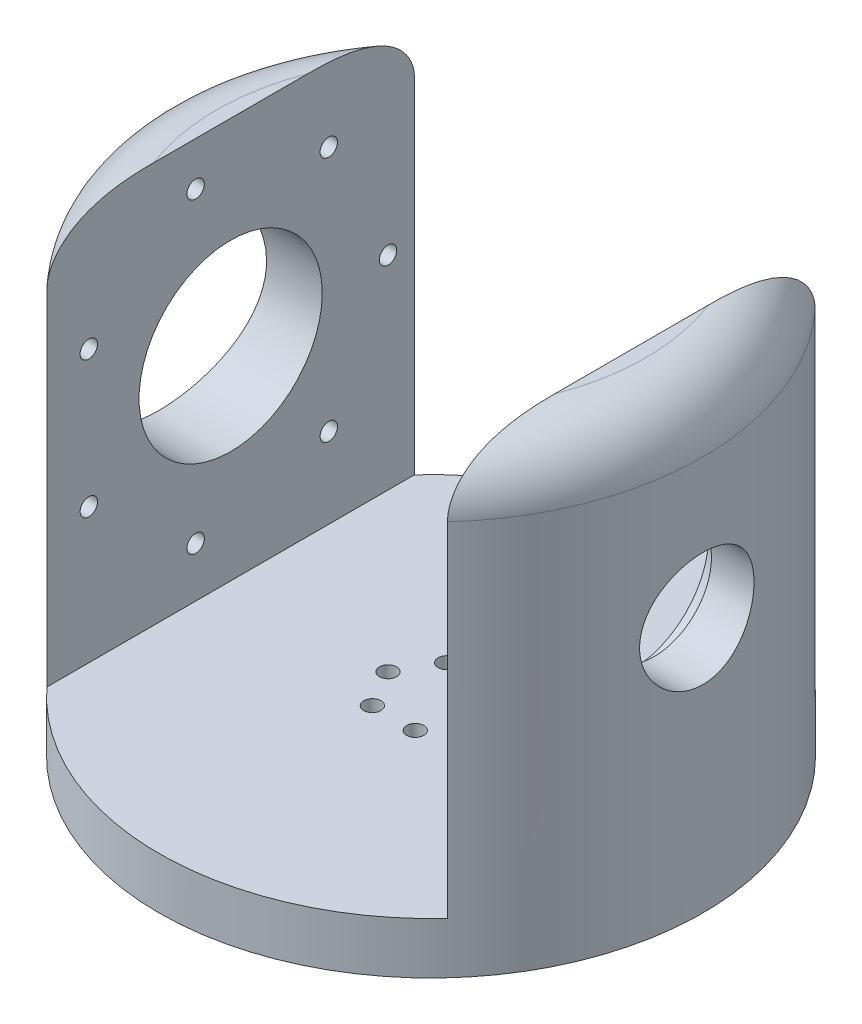
SolidWorks part; units mm, degrees
ref_plane "Alzado" through (0, 0, 0) normal (0, 0, 1) x (1, 0, 0)
ref_plane "Planta" through (0, 0, 0) normal (0, 1, 0) x (1, 0, 0)
ref_plane "Vista lateral" through (0, 0, 0) normal (1, 0, 0) x (0, 0, -1)
sketch "Croquis1" plane through (0, 0, 0) normal (0, 1, 0) x (1, 0, 0)
  circle A0 centre (0, 0) radius 47.5
  circle A1 centre (0, 0) radius 10
  dimension "D1" = 95
  dimension "D2" = 20
extrude "Saliente-Extruir1" add sketch "Croquis1" along normal blind 6
sketch "Croquis2" plane through (0, 6, 0) normal (0, 1, 0) x (1, 0, 0)
  circle A0 centre (0, 0) radius 47.5
  circle A1 centre (0, 0) radius 7.5 construction
  circle A2 centre (7.5, 0) radius 1.5
  circle A3 centre (3.75, -6.4952) radius 1.5
  circle A4 centre (-3.75, -6.4952) radius 1.5
  circle A5 centre (-7.5, 0) radius 1.5
  circle A6 centre (-3.75, 6.4952) radius 1.5
  circle A7 centre (3.75, 6.4952) radius 1.5
  point P18 (0, 0)
  dimension "D1" = 95
  dimension "D2" = 15
  dimension "D3" = 3
  dimension "D4" = 6
extrude "Saliente-Extruir2" add sketch "Croquis2" along normal blind 3
sketch "Croquis3" plane through (0, 0, 0) normal (0, -1, 0) x (1, 0, 0)
  circle A0 centre (0, 0) radius 45
  circle A1 centre (0, 0) radius 32.5
  dimension "D1" = 90
  dimension "D2" = 65
extrude "Cortar-Extruir1" cut sketch "Croquis3" against normal blind 3
sketch "Croquis4" plane through (0, 0, 0) normal (0, -1, 0) x (1, 0, 0)
  circle A0 centre (0, 0) radius 13.5
  dimension "D1" = 27
extrude "Cortar-Extruir2" cut sketch "Croquis4" against normal blind 4
sketch "Croquis5" plane through (0, 9, 0) normal (0, 1, 0) x (1, 0, 0)
  line L0 (35, 32.1131) -> (35, -32.1131)
  line L1 (-35, 32.1131) -> (-35, -32.1131)
  arc A0 (-35, 32.1131) -> (-35, -32.1131) centre (0, 0) ccw
  arc A1 (35, -32.1131) -> (35, 32.1131) centre (0, 0) ccw
  dimension "D1" = 95
  dimension "D2" = 35
  dimension "D3" = 64.2262
extrude "Saliente-Extruir4" add sketch "Croquis5" along normal blind 70
fillet "Redondeo1" radius 10 2 edges at (-47.5, 79, 0) (47.5, 79, 0)
sketch "Croquis6" plane through (35, 0, 0) normal (-1, 0, 0) x (0, 0, 1)
  line L0 (-32.1131, 9) -> (32.1131, 9) construction
  line L1 (0, 9) -> (0, 79) construction
  line L2 (13.4629, 79) -> (-13.4629, 79) construction
  circle A1 centre (0, 44) radius 13.5
  dimension "D2" = 27
extrude "Cortar-Extruir3" cut sketch "Croquis6" against normal blind 4
sketch "Croquis7" plane through (35, 0, 0) normal (-1, 0, 0) x (0, 0, 1)
  line L0 (0, 10.1089) -> (0, 79) construction
  line L1 (13.4629, 79) -> (-13.4629, 79) construction
  circle A0 centre (0, 44.5544) radius 10
  dimension "D2" = 20
  dimension "D1" = 44.5544
extrude "Cortar-Extruir4" cut sketch "Croquis7" against normal through all
sketch "Croquis8" plane through (35, 0, 0) normal (-1, 0, 0) x (0, 0, 1)
  line L1 (0, 9) -> (0, 79) construction
  line L2 (13.4629, 79) -> (-13.4629, 79) construction
  circle A0 centre (0, 44.5) radius 23.5
  circle A1 centre (0, 44.5) radius 15
  dimension "D1" = 47
  dimension "D2" = 30
  dimension "D3" = 44.5
extrude "Cortar-Extruir5" cut sketch "Croquis8" against normal blind 2
sketch "Croquis10" plane through (-35, 0, 0) normal (1, 0, 0) x (0, 0, -1)
  circle A0 centre (0, 44.5544) radius 16
  dimension "D1" = 32
  dimension "D2" = 44.5544
extrude "Cortar-Extruir6" cut sketch "Croquis10" against normal through all
sketch "Croquis12" plane through (-35, 0, 0) normal (1, 0, 0) x (0, 0, -1)
  circle A1 centre (27.5, 44.5544) radius 1.52
  circle A2 centre (17.1494, 23.0524) radius 1.52
  circle A3 centre (-6.115, 17.7385) radius 1.52
  circle A4 centre (-24.7747, 32.6142) radius 1.52
  circle A5 centre (-24.7786, 56.4778) radius 1.52
  circle A6 centre (-6.1236, 71.3595) radius 1.52
  circle A7 centre (17.1425, 66.0531) radius 1.52
  point P0 (0, 0)
  dimension "D1" = 44.5544
  dimension "D2" = 3.04
  dimension "D4" = 27.5
  dimension "D3" = 7
extrude "Cortar-Extruir8" cut sketch "Croquis12" against normal through all
